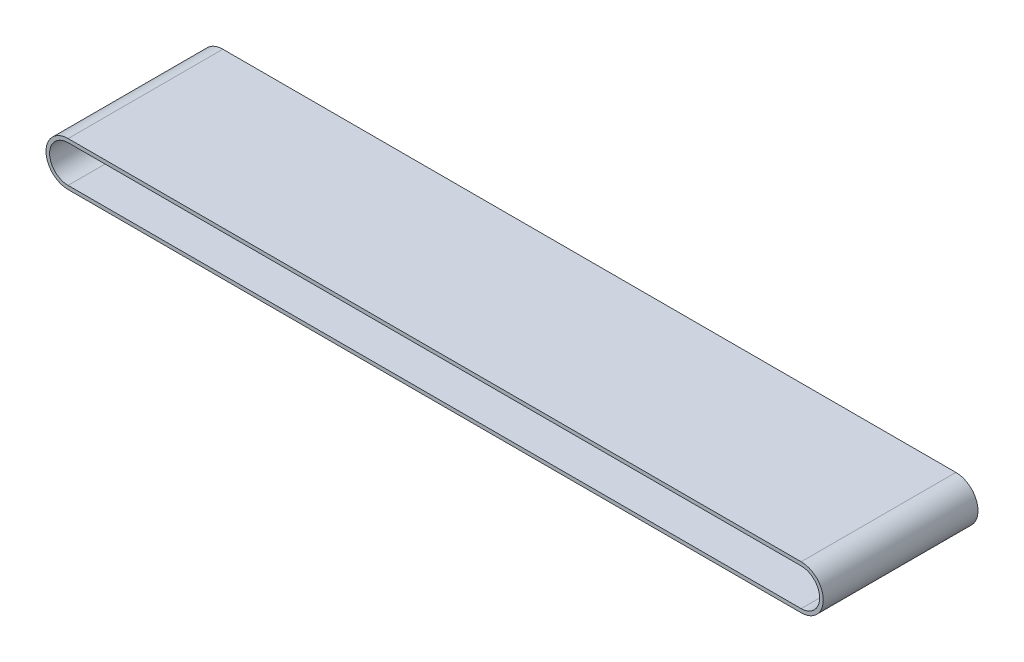
SolidWorks part; units mm, degrees
ref_plane "Front Plane" through (0, 0, 0) normal (0, 0, 1) x (1, 0, 0)
ref_plane "Top Plane" through (0, 0, 0) normal (0, 1, 0) x (1, 0, 0)
ref_plane "Right Plane" through (0, 0, 0) normal (1, 0, 0) x (0, 0, -1)
sketch "Sketch1" plane through (0, 0, 0) normal (0, 0, 1) x (1, 0, 0)
  line L0 (-2517.4302, 0) -> (2537.5698, 0)
  line L1 (-2517.4302, -255) -> (2537.5698, -255)
  line L2 (-2517.4302, 25) -> (2537.5698, 25)
  line L3 (-2517.4302, -280) -> (2537.5698, -280)
  arc A0 (-2517.4302, 0) -> (-2517.4302, -255) centre (-2517.4302, -127.5) ccw
  arc A1 (2537.5698, 0) -> (2537.5698, -255) centre (2537.5698, -127.5) cw
  arc A2 (2537.5698, 25) -> (2537.5698, -280) centre (2537.5698, -127.5) cw
  arc A3 (-2517.4302, 25) -> (-2517.4302, -280) centre (-2517.4302, -127.5) ccw
  dimension "D3" = 255
  dimension "D1" = 5055
  dimension "D2" = 25
extrude "Boss-Extrude1" add sketch "Sketch1" along normal blind 1067
